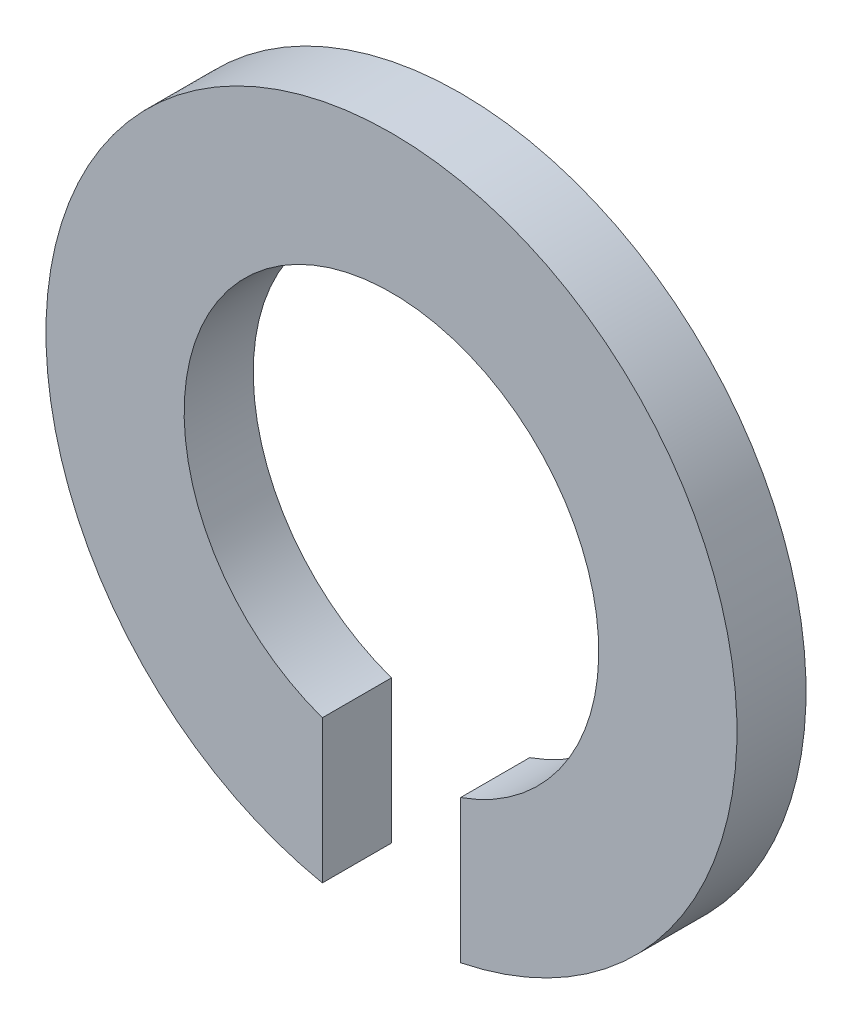
SolidWorks part; units mm, degrees
ref_plane "Plan de face" through (0, 0, 0) normal (0, 0, 1) x (1, 0, 0)
ref_plane "Plan de dessus" through (0, 0, 0) normal (0, 1, 0) x (1, 0, 0)
ref_plane "Plan de droite" through (0, 0, 0) normal (1, 0, 0) x (0, 0, -1)
sketch "Esquisse2" plane through (0, 0, 0) normal (0, 0, 1) x (1, 0, 0)
  line L0 (0, 0) -> (0, -4.3237) construction
  line L1 (0.5, -2.4495) -> (0.5, -1.4142)
  line L2 (-0.5, -2.4495) -> (-0.5, -1.4142)
  arc A0 (0.5, -1.4142) -> (-0.5, -1.4142) centre (0, 0) ccw
  arc A1 (0.5, -2.4495) -> (-0.5, -2.4495) centre (0, 0) ccw
  dimension "D1" = 3
  dimension "D2" = 5
  dimension "D3" = 0.5
extrude "Boss.-Extru.1" add sketch "Esquisse2" along normal blind 0.5
